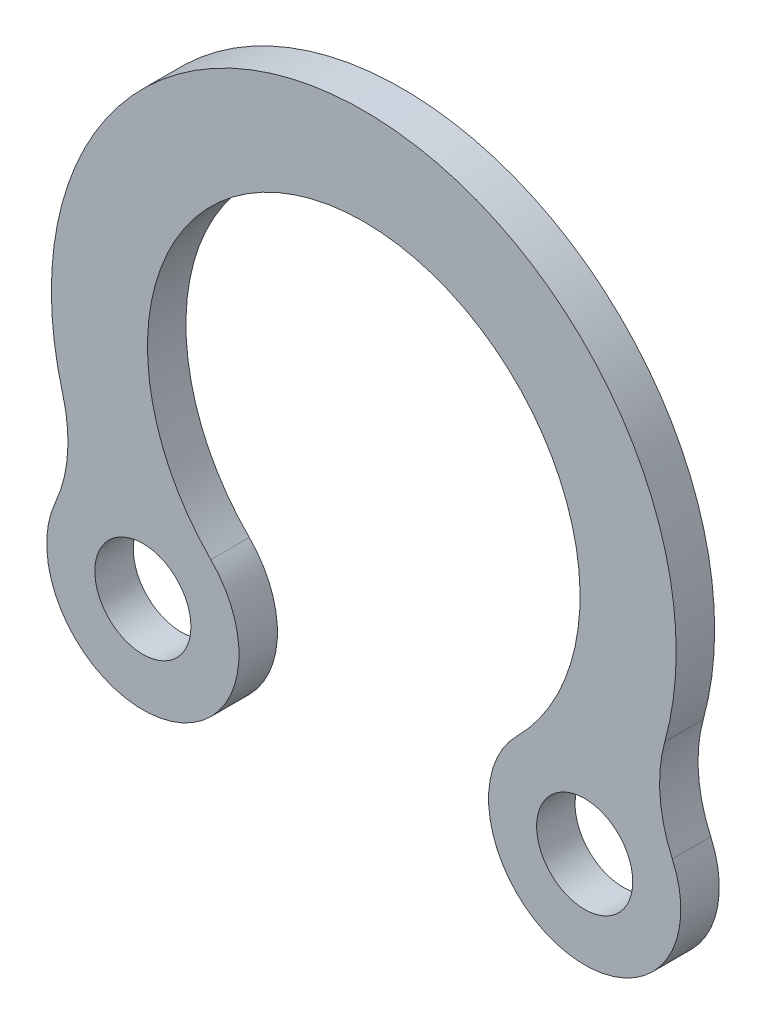
SolidWorks part; units mm, degrees
material "AISI 1035 Steel (SS)"
ref_plane "Front Plane" through (0, 0, 0) normal (0, 0, 1) x (1, 0, 0)
ref_plane "Top Plane" through (0, 0, 0) normal (0, 1, 0) x (1, 0, 0)
ref_plane "Right Plane" through (0, 0, 0) normal (1, 0, 0) x (0, 0, -1)
sketch "Sketch1" plane through (0, 0, 0) normal (0, 0, 1) x (1, 0, 0)
  circle A0 centre (0, 0) radius 6.5
  circle A1 centre (0, 0) radius 4.5
  dimension "D1" = 9
  dimension "D2" = 13
extrude "Boss-Extrude1" add sketch "Sketch1" along normal blind 0.8
sketch "Sketch2" plane through (0, 0, 0.8) normal (0, 0, 1) x (1, 0, 0)
  line L0 (0, 0) -> (-4.5962, -4.5962) construction
  line L1 (0, 0) -> (0, -6.5) construction
  line L2 (0, 0) -> (4.5962, -4.5962) construction
  circle A0 centre (0, 0) radius 6.5 construction
  circle A1 centre (-4.5962, -4.5962) radius 2
  circle A2 centre (4.5962, -4.5962) radius 2
  circle A3 centre (0, 0) radius 4.5 construction
  dimension "D1" = 45
  dimension "D2" = 45
extrude "Boss-Extrude2" add sketch "Sketch2" against normal blind 0.8
sketch "Sketch3" plane through (0, 0, 0.8) normal (0, 0, 1) x (1, 0, 0)
  arc A0 (-2.9812, -5.776) -> (-3.182, -3.182) centre (-4.5962, -4.5962) ccw
  arc A1 (3.182, -3.182) -> (2.9812, -5.776) centre (4.5962, -4.5962) ccw
  circle A2 centre (0, 0) radius 4.5 construction
  arc A3 (-3.182, -3.182) -> (3.182, -3.182) centre (0, 0) ccw
  arc A4 (-2.9812, -5.776) -> (2.9812, -5.776) centre (0, 0) ccw construction
  arc A5 (-2.9812, -5.776) -> (2.9812, -5.776) centre (0, 0) ccw
extrude "Cut-Extrude1" cut sketch "Sketch3" against normal blind 0.8
sketch "Sketch4" plane through (0, 0, 0.8) normal (0, 0, 1) x (1, 0, 0)
  circle A0 centre (-4.5962, -4.5962) radius 1
  circle A1 centre (4.5962, -4.5962) radius 1
  dimension "D1" = 2
  dimension "D2" = 2
extrude "Cut-Extrude2" cut sketch "Sketch4" against normal blind 0.8
fillet "Fillet1" radius 3 2 edges at (-5.776, -2.9812, 0.4) (5.776, -2.9812, 0.4)
